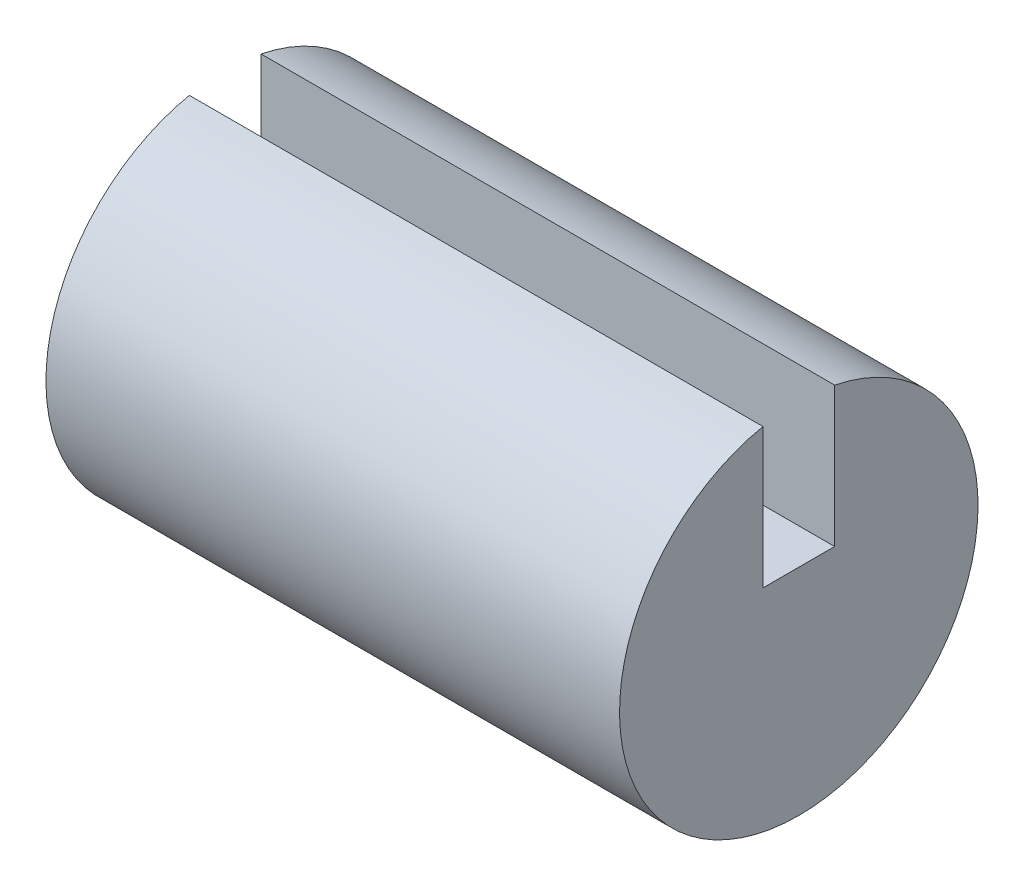
SolidWorks part; units mm, degrees
ref_plane "前视基准面" through (0, 0, 0) normal (0, 0, 1) x (1, 0, 0)
ref_plane "上视基准面" through (0, 0, 0) normal (0, 1, 0) x (1, 0, 0)
ref_plane "右视基准面" through (0, 0, 0) normal (1, 0, 0) x (0, 0, -1)
sketch "草图1" plane through (0, 0, 0) normal (1, 0, 0) x (0, 0, -1)
  circle A0 centre (0, 0) radius 2.5
  dimension "D1" = 5
extrude "凸台-拉伸1" add sketch "草图1" along normal blind 8
sketch "草图2" plane through (0, 0, 0) normal (0, 1, 0) x (1, 0, 0)
  line L0 (0, 0) -> (8, 0) construction
  line L1 (8, -2.5) -> (8, 2.5) construction
  line L2 (4, 0) -> (4, -2.5) construction
  line L3 (0, -2.5) -> (8, -2.5) construction
  circle A0 centre (4, 0) radius 0.5
  dimension "D1" = 1
extrude "切除-拉伸2" cut sketch "草图2" against normal mid plane 8
sketch "草图3" plane through (8, 0, 0) normal (1, 0, 0) x (0, 0, -1)
  line L0 (0, 0) -> (2.8806, 0) construction
  line L1 (0, 0) -> (0, 2.5) construction
  line L3 (-0.5, 4.5) -> (0.5, 4.5)
  line L4 (-0.5, 4.5) -> (-0.5, 0.5)
  line L5 (-0.5, 0.5) -> (0.5, 0.5)
  line L6 (0.5, 4.5) -> (0.5, 0.5)
  line L7 (-0.5, 4.5) -> (0.5, 0.5) construction
  line L8 (-0.5, 0.5) -> (0.5, 4.5) construction
  circle A0 centre (0, 0) radius 2.5 construction
  dimension "D1" = 1
  dimension "D2" = 4
extrude "切除-拉伸3" cut sketch "草图3" against normal blind 8
